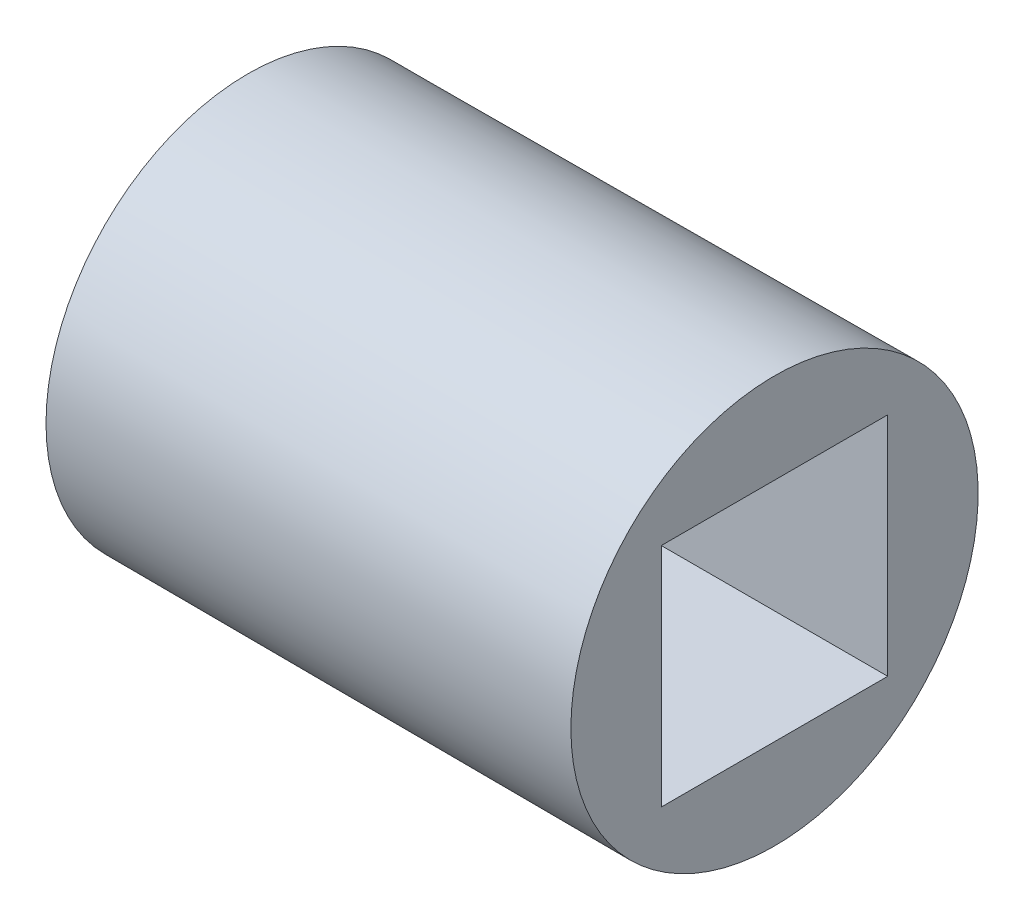
SolidWorks part; units mm, degrees
ref_plane "Front Plane" through (0, 0, 0) normal (0, 0, 1) x (1, 0, 0)
ref_plane "Top Plane" through (0, 0, 0) normal (0, 1, 0) x (1, 0, 0)
ref_plane "Right Plane" through (0, 0, 0) normal (1, 0, 0) x (0, 0, -1)
sketch "Sketch1" plane through (0, 0, 0) normal (0, 0, 1) x (1, 0, 0)
  line L0 (-25.6498, 0) -> (-25.6498, -11.5)
  line L1 (55, 0) -> (-55, 0) construction
  line L2 (-25.6498, 0) -> (4.3502, 0)
  line L3 (4.3502, 0) -> (4.3502, -11.6)
  line L4 (4.3502, -11.6) -> (-25.6498, -11.5)
  dimension "D1" = 11.5
  dimension "D2" = 11.6
revolve "Revolve1" add sketch "Sketch1" angle 360 about L2
sketch "Sketch2" plane through (4.3502, 0, 0) normal (1, 0, 0) x (0, 0, -1)
  line L0 (6.45, 6.45) -> (-6.45, 6.45)
  line L4 (-6.45, 6.45) -> (-6.45, -6.45)
  line L5 (-6.45, -6.45) -> (6.45, -6.45)
  line L6 (6.45, -6.45) -> (6.45, 6.45)
  dimension "D3" = 12.9
  dimension "D4" = 12.9
extrude "Cut-Extrude1" cut sketch "Sketch2" against normal blind 25
